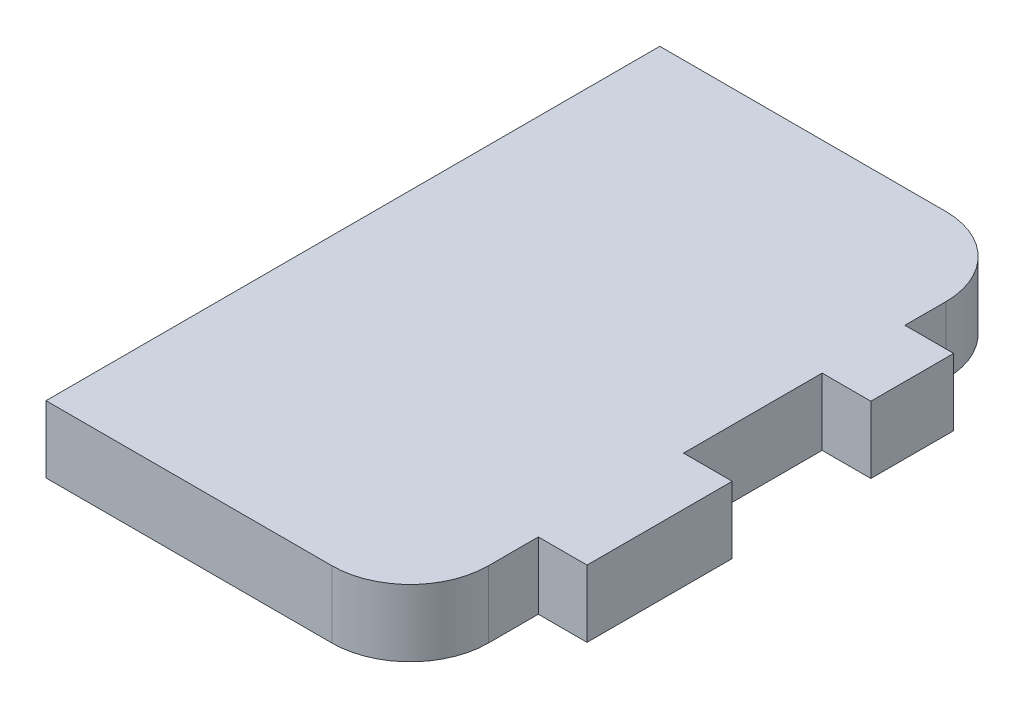
SolidWorks part; units mm, degrees
ref_plane "Front Plane" through (0, 0, 0) normal (0, 0, 1) x (1, 0, 0)
ref_plane "Top Plane" through (0, 0, 0) normal (0, 1, 0) x (1, 0, 0)
ref_plane "Right Plane" through (0, 0, 0) normal (1, 0, 0) x (0, 0, -1)
sketch "Sketch1" plane through (0, 0, 0) normal (0, 1, 0) x (1, 0, 0)
  line L1 (0, 0) -> (37, 0)
  line L2 (0, 0) -> (0, 55)
  line L3 (0, 55) -> (37, 55)
  line L4 (37, 0) -> (37, 55)
  dimension "D1" = 55
  dimension "D2" = 37
extrude "Boss-Extrude1" add sketch "Sketch1" along normal blind 6
sketch "Sketch2" plane through (0, 6, 0) normal (0, 1, 0) x (1, 0, 0)
  line L0 (37, 0) -> (37, 55) construction
  line L1 (37, 44.3329) -> (32.634, 44.3329)
  line L2 (37, 44.3329) -> (37, 55)
  line L3 (37, 55) -> (32.634, 55)
  line L4 (32.634, 44.3329) -> (32.634, 55)
  line L5 (37, 55) -> (0, 55) construction
  line L6 (0, 0) -> (37, 0) construction
  line L7 (37, 36.9152) -> (32.634, 36.9152)
  line L8 (37, 36.9152) -> (37, 24.4926)
  line L9 (37, 24.4926) -> (32.634, 24.4926)
  line L10 (32.634, 36.9152) -> (32.634, 24.4926)
  line L11 (37, 11.4834) -> (32.634, 11.4834)
  line L12 (37, 11.4834) -> (37, 0)
  line L13 (37, 0) -> (32.634, 0)
  line L14 (32.634, 11.4834) -> (32.634, 0)
extrude "Cut-Extrude1" cut sketch "Sketch2" against normal through all
fillet "Fillet1" radius 7 2 edges at (32.634, 3, 0) (32.634, 3, -55)
